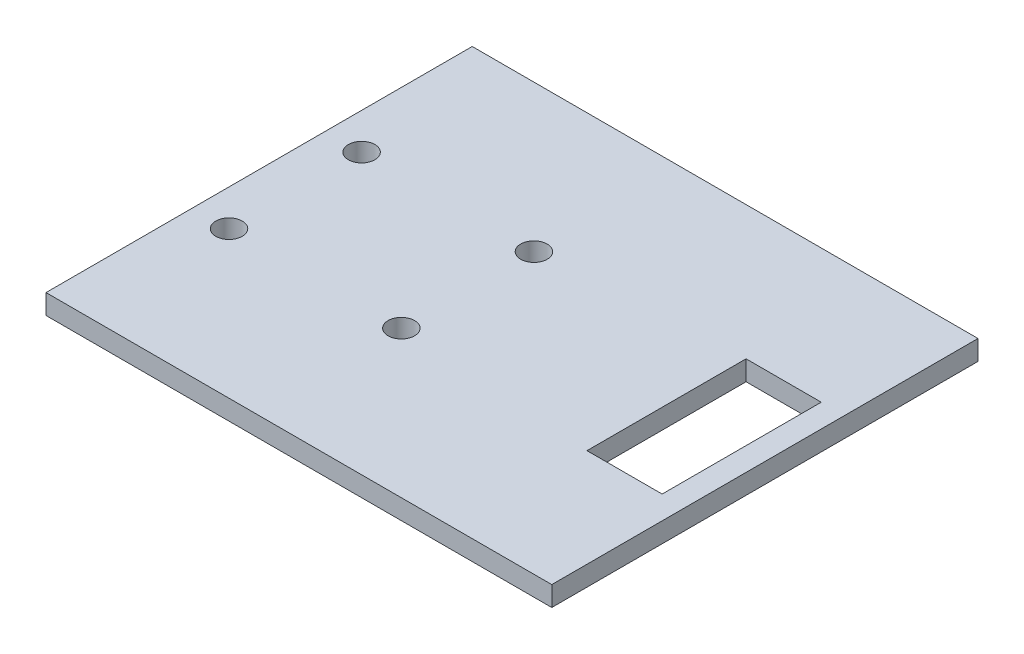
SolidWorks part; units mm, degrees
ref_plane "Frontal Plane" through (0, 0, 0) normal (0, 0, 1) x (1, 0, 0)
ref_plane "Horizontal Plane" through (0, 0, 0) normal (0, 1, 0) x (1, 0, 0)
ref_plane "Profile Plane" through (0, 0, 0) normal (1, 0, 0) x (0, 0, -1)
sketch "Sketch1" plane through (0, 0, 0) normal (0, 1, 0) x (1, 0, 0)
  line L1 (0, 0) -> (76.3, 0)
  line L2 (0, 0) -> (0, -64.3)
  line L3 (0, -64.3) -> (76.3, -64.3)
  line L4 (76.3, 0) -> (76.3, -64.3)
  dimension "D1" = 76.3
  dimension "D2" = 64.3
extrude "Boss-Extrude1" add sketch "Sketch1" along normal blind 3
sketch "Sketch4" plane through (0, 3, 0) normal (0, 1, 0) x (1, 0, 0)
  line L0 (3.4598, -11.8474) -> (3.4598, -49.9573) construction
  line L1 (72.8, -20.15) -> (72.8, -44.15)
  line L2 (61.4598, -20.15) -> (72.8, -20.15)
  line L3 (0, 0) -> (0, -64.3) construction
  line L4 (61.4598, -20.15) -> (61.4598, -44.15)
  line L5 (61.4598, -44.15) -> (72.8, -44.15)
  line L8 (76.3, -64.3) -> (76.3, 0) construction
  circle A0 centre (5.4598, -22.15) radius 2
  circle A1 centre (31.4598, -22.15) radius 2
  circle A2 centre (5.4598, -42.15) radius 2
  circle A4 centre (31.4598, -42.15) radius 2
  point P13 (0, -32.15)
  dimension "D1" = 4
  dimension "D2" = 10
  dimension "D3" = 10
  dimension "D4" = 10
  dimension "D5" = 10
  dimension "D6" = 26
  dimension "D7" = 26
  dimension "D8" = 12
  dimension "D9" = 3.5
  dimension "D10" = 12
  dimension "D11" = 30
extrude "Cut-Extrude2" cut sketch "Sketch4" against normal through all
